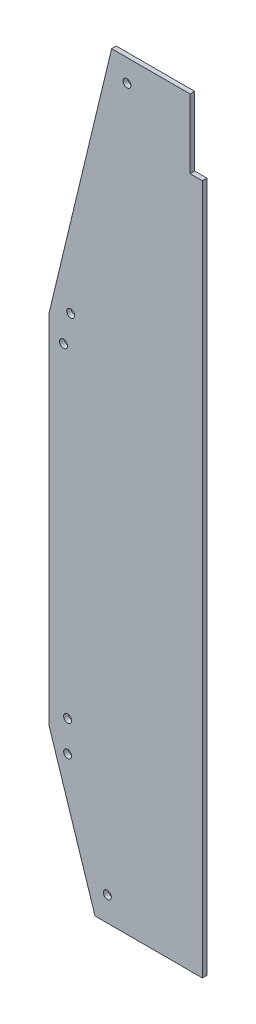
SolidWorks part; units mm, degrees
ref_plane "Plan de face" through (0, 0, 0) normal (0, 0, 1) x (1, 0, 0)
ref_plane "Plan de dessus" through (0, 0, 0) normal (0, 1, 0) x (1, 0, 0)
ref_plane "Plan de droite" through (0, 0, 0) normal (1, 0, 0) x (0, 0, -1)
sketch "Esquisse1" plane through (0, 0, 0) normal (0, 0, 1) x (1, 0, 0)
  line L0 (0, 450.3) -> (-8, 450.3)
  line L1 (0, 0) -> (-70, 0)
  line L2 (0, 0) -> (0, 450.3)
  line L3 (-8, 495.3) -> (-59.18, 495.3)
  line L4 (-100, 92.65) -> (-100, 325.5)
  line L5 (-8, 450.3) -> (-8, 495.3)
  line L6 (-59.18, 495.3) -> (-100, 325.5)
  line L8 (-70, 0) -> (-100, 92.65)
  dimension "D1" = 100
  dimension "D2" = 495.3
  dimension "D3" = 8
  dimension "D4" = 45
  dimension "D5" = 51.18
  dimension "D6" = 169.8
  dimension "D7" = 92.65
  dimension "D8" = 70
extrude "Boss.-Extru.1" add sketch "Esquisse1" along normal blind 3
sketch "Esquisse2" plane through (0, 0, 0) normal (0, 0, -1) x (-1, 0, 0)
  circle A12 centre (61.9697, 16) radius 2.6 construction
  circle A13 centre (87.8656, 82.65) radius 2.6 construction
  circle A14 centre (87.8656, 102.65) radius 2.6 construction
  circle A15 centre (85.8606, 332.4181) radius 2.6 construction
  circle A16 centre (90.5354, 312.9721) radius 2.6 construction
  circle A17 centre (49.1687, 480.768) radius 2.6 construction
  circle A18 centre (61.9697, 16) radius 2.6
  circle A19 centre (87.8656, 82.65) radius 2.6
  circle A20 centre (87.8656, 102.65) radius 2.6
  circle A21 centre (85.8606, 332.4181) radius 2.6
  circle A22 centre (90.5354, 312.9721) radius 2.6
  circle A23 centre (49.1687, 480.768) radius 2.6
extrude "Enlèv. mat.-Extru.1" cut sketch "Esquisse2" against normal blind 20
